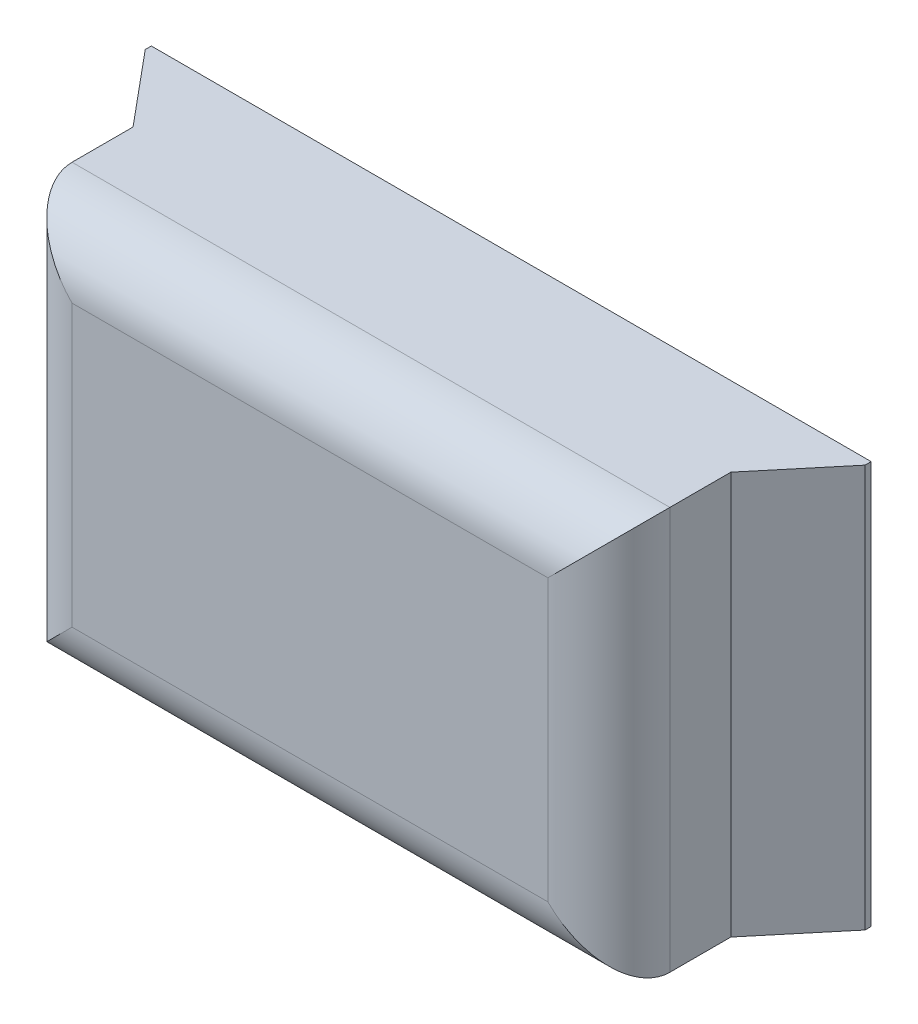
SolidWorks part; units mm, degrees
material "ABS"
ref_plane "Front Plane" through (0, 0, 0) normal (0, 0, 1) x (1, 0, 0)
ref_plane "Top Plane" through (0, 0, 0) normal (0, 1, 0) x (1, 0, 0)
ref_plane "Right Plane" through (0, 0, 0) normal (1, 0, 0) x (0, 0, -1)
sketch "Sketch1" plane through (0, 0, 0) normal (0, 1, 0) x (1, 0, 0)
  line L1 (-19.1544, -8.8976) -> (-14.2544, -8.8976)
  line L2 (-19.6544, -7.2976) -> (-19.6544, -7.2476)
  line L3 (-19.6544, -7.2476) -> (-13.7544, -7.2476)
  line L5 (-19.1544, -7.8976) -> (-19.6544, -7.2976)
  line L6 (-19.1544, -7.8976) -> (-19.1544, -8.8976)
  line L8 (-14.2544, -7.8976) -> (-14.2544, -8.8976)
  line L9 (-14.2544, -7.8976) -> (-13.7544, -7.2976)
  line L10 (-13.7544, -7.2976) -> (-13.7544, -7.2476)
  point P0 (0, 0)
extrude "Boss-Extrude1" add sketch "Sketch1" along normal blind 3.3
fillet "Fillet1" radius 0.5 4 edges at (-19.1544, 1.65, 8.8976) (-16.7044, 3.3, 8.8976) (-14.2544, 1.65, 8.8976) (-16.7044, 0, 8.8976)
sketch "Sketch2" plane through (0, 0, 7.2476) normal (0, 0, -1) x (-1, 0, 0)
  line L0 (16.7044, 0) -> (16.7044, 3.3) construction
  line L1 (13.7544, 0) -> (19.6544, 0) construction
  line L2 (13.7544, 3.3) -> (19.6544, 3.3) construction
  line L4 (15.4686, 2.75) -> (17.9402, 2.75)
  line L5 (15.4686, 2.75) -> (15.4686, 0.55)
  line L6 (15.4686, 0.55) -> (17.9402, 0.55)
  line L7 (17.9402, 2.75) -> (17.9402, 0.55)
  line L8 (15.4686, 2.75) -> (17.9402, 0.55) construction
  line L9 (15.4686, 0.55) -> (17.9402, 2.75) construction
  point P6 (16.7044, 1.65)
extrude "Cut-Extrude1" cut sketch "Sketch2" against normal blind 0.46
